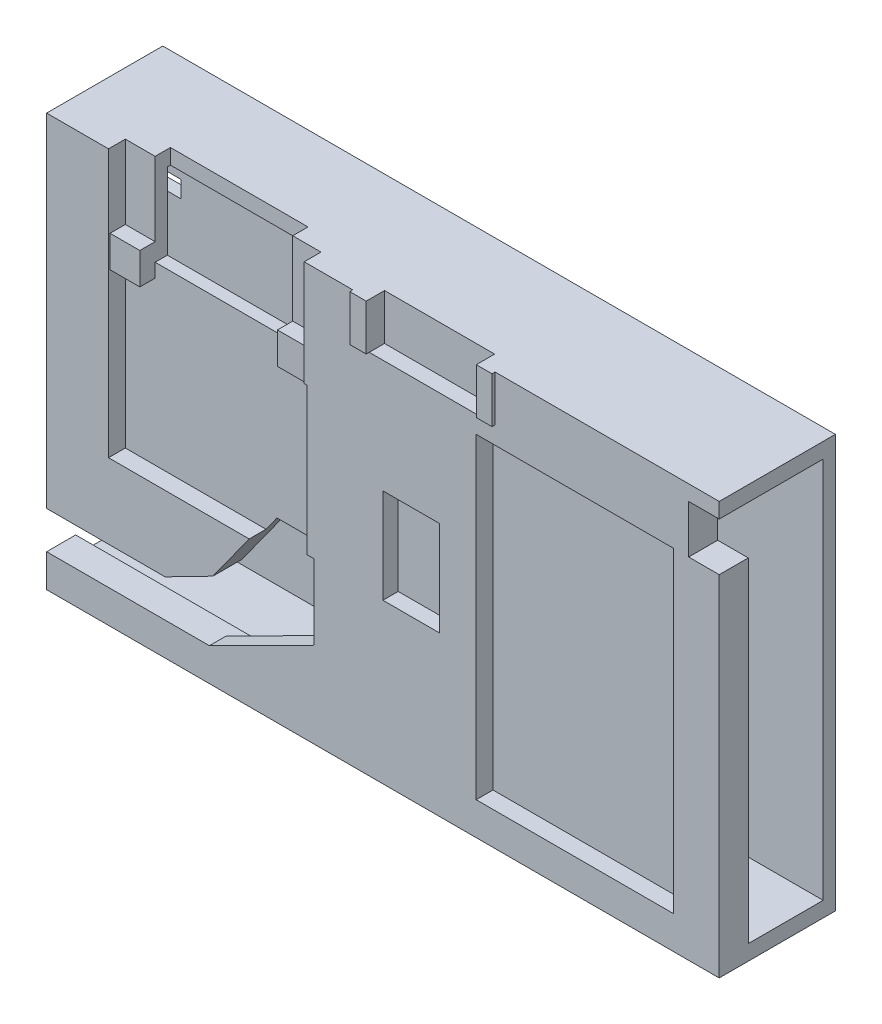
SolidWorks part; units mm, degrees
ref_plane "Plan de face" through (0, 0, 0) normal (0, 0, 1) x (1, 0, 0)
ref_plane "Plan de dessus" through (0, 0, 0) normal (0, 1, 0) x (1, 0, 0)
ref_plane "Plan de droite" through (0, 0, 0) normal (1, 0, 0) x (0, 0, -1)
sketch "Esquisse1" plane through (0, 0, 0) normal (0, 0, 1) x (1, 0, 0)
  line L1 (-22, -12.5) -> (22, -12.5)
  line L2 (-22, -12.5) -> (-22, 12.5)
  line L3 (-22, 12.5) -> (22, 12.5)
  line L4 (22, -12.5) -> (22, 12.5)
  line L5 (-22, -12.5) -> (22, 12.5) construction
  line L6 (-22, 12.5) -> (22, -12.5) construction
  point P0 (0, 0)
  dimension "D1" = 44
  dimension "D2" = 25
extrude "Boss.-Extru.1" add sketch "Esquisse1" along normal blind 1.9
sketch "Esquisse2" plane through (0, 0, 1.9) normal (0, 0, 1) x (1, 0, 0)
  line L0 (-22, 12.5) -> (-22, -12.5) construction
  line L1 (22, -12.5) -> (22, 12.5) construction
  line L3 (0.5, -12.5) -> (1.5, -12.5)
  line L11 (-2.5, 12.5014) -> (-20.5, 12.5014)
  line L12 (-2.5, 12.5014) -> (-2.5, -8.8986)
  line L13 (-2.5, -8.8986) -> (-20.5, -8.8986)
  line L14 (-20.5, 12.5014) -> (-20.5, -8.8986)
  line L16 (6.1, -11.3493) -> (19, -11.3493)
  line L17 (6.1, -11.3493) -> (6.1, 9.3507)
  line L18 (6.1, 9.3507) -> (19, 9.3507)
  line L19 (19, -11.3493) -> (19, 9.3507)
  line L20 (6.1, -11.3493) -> (19, 9.3507) construction
  line L21 (6.1, 9.3507) -> (19, -11.3493) construction
  point P5 (1, 0)
  point P19 (12.55, -0.9993)
  dimension "D1" = 18
  dimension "D2" = 1.5
  dimension "D3" = 3
  dimension "D4" = 12.9
  dimension "D5" = 20.7
extrude "Enlèv. mat.-Extru.1" cut sketch "Esquisse2" against normal blind 1.1 contours L12 L11 L14 L13 | L17 L16 L19 L18
sketch "Esquisse3" plane through (0, 0, 0.8) normal (0, 0, 1) x (1, 0, 0)
  line L0 (-20.5, 12.5) -> (-2.5, -8.8986)
  line L1 (-2.5, -8.8986) -> (-20.5, -8.8986)
  line L2 (-20.5, -8.8986) -> (-2.5, 12.5)
  line L3 (-2.5, 12.5) -> (-11.5, 1.8007)
  line L4 (-11.5, 1.8007) -> (-11.5, 14.3281)
  line L5 (-2.5, 12.5) -> (-20.5, 12.5) construction
  line L6 (-16, 18.5) -> (-7, 18.5)
  line L7 (-16, 18.5) -> (-16, 6.5)
  line L8 (-16, 6.5) -> (-7, 6.5)
  line L9 (-7, 18.5) -> (-7, 6.5)
  line L10 (-16, 18.5) -> (-7, 6.5) construction
  line L11 (-16, 6.5) -> (-7, 18.5) construction
  point P6 (-11.5, 12.5)
  dimension "D1" = 9
  dimension "D2" = 12
extrude "Enlèv. mat.-Extru.2" cut sketch "Esquisse3" against normal blind 10 contours L7 L6 L9 L8
sketch "Esquisse4" plane through (0, 0, 1.9) normal (0, 0, 1) x (1, 0, 0)
  line L0 (-2.5, -8.8986) -> (-2.5, -14.0676)
  line L1 (-4.5, -15.1841) -> (-4.5, -4.4659)
  line L2 (-8, -15.1841) -> (-8, -5.4707)
  line L3 (-19.2974, -5.6986) -> (1.333, -5.6986)
  line L4 (-2.5, -8.8986) -> (-20.5, -8.8986) construction
  line L5 (-22, -12.5) -> (22, -12.5) construction
  line L6 (-4.5, -5.6986) -> (-8, -5.6986)
  line L7 (-4.5, -5.6986) -> (-4.5, -12.5)
  line L8 (-4.5, -12.5) -> (-8, -12.5)
  line L9 (-8, -5.6986) -> (-8, -12.5)
  dimension "D1" = 2
  dimension "D2" = 3.5
  dimension "D3" = 3.2
extrude "Enlèv. mat.-Extru.3" cut sketch "Esquisse4" against normal blind 1.4 contours L7 L6 L9 L8
sketch "Esquisse5" plane through (0, 0, 1.9) normal (0, 0, 1) x (1, 0, 0)
  line L3 (-22, -12.5) -> (-8, -12.5) construction
  line L6 (-22, 12.5) -> (-22, -12.5) construction
  line L13 (-8, -5.6986) -> (-14.25, -8.8986)
  line L14 (-8, -8.8986) -> (-20.5, -8.8986) construction
  line L15 (-14.25, -8.8986) -> (-22, -8.8986)
  line L16 (-22, -8.8986) -> (-22, -12.5)
  line L17 (-4.5, -12.5) -> (-4.5, -5.6986)
  line L18 (-4.5, -5.6986) -> (-8, -5.6986)
  line L21 (-22, -12.5) -> (-4.5, -12.5)
extrude "Enlèv. mat.-Extru.4" cut sketch "Esquisse5" against normal blind 2.4
sketch "Esquisse6" plane through (0, 6.5, 0) normal (0, 1, 0) x (1, 0, 0)
  line L1 (-16, 0) -> (-7, 0)
  line L2 (-16, 0) -> (-16, -0.8)
  line L3 (-16, -0.8) -> (-7, -0.8)
  line L4 (-7, 0) -> (-7, -0.8)
extrude "Boss.-Extru.2" add sketch "Esquisse6" along normal blind 1
sketch "Esquisse7" plane through (0, -8.8986, 0) normal (0, 1, 0) x (1, 0, 0)
  line L0 (-2.5, -0.8) -> (-4.5, -0.8) construction
  line L1 (-2.5, -0.8) -> (-4.5, -0.8)
  line L2 (-2.5, -0.8) -> (-2.5, -1.9)
  line L3 (-2.5, -1.9) -> (-4.5, -1.9)
  line L4 (-4.5, -0.8) -> (-4.5, -1.9)
  line L5 (-2.5, -0.8) -> (-2.5, -1.9) construction
extrude "Boss.-Extru.3" add sketch "Esquisse7" along normal blind 1
sketch "Esquisse9" plane through (0, 12.5, 0) normal (0, 1, 0) x (1, 0, 0)
  line L1 (22, 0) -> (-2.5, 0)
  line L2 (22, 0) -> (22, -1.9)
  line L3 (22, -1.9) -> (-2.5, -1.9)
  line L4 (-2.5, -0.8) -> (-2.5, -1.9)
  line L5 (-7, 0) -> (-2.5, 0)
  line L6 (-7, 0) -> (-7, -0.8)
  line L7 (-7, -0.8) -> (-2.5, -0.8)
  line L9 (-22, 0) -> (-20.5, 0)
  line L10 (-22, 0) -> (-22, -1.9)
  line L11 (-22, -1.9) -> (-20.5, -1.9)
  line L12 (-20.5, -0.8) -> (-20.5, -1.9)
  line L13 (-16, -0.8) -> (-20.5, -0.8)
  line L14 (-16, -0.8) -> (-16, 0)
  line L15 (-16, 0) -> (-20.5, 0)
extrude "Boss.-Extru.4" add sketch "Esquisse9" along normal blind 1
sketch "Esquisse12" plane through (0, -12.5, 0) normal (0, -1, 0) x (1, 0, 0)
  line L1 (-4.5, 1.9) -> (22, 1.9)
  line L2 (-4.5, 1.9) -> (-4.5, 0)
  line L3 (-4.5, 0) -> (22, 0)
  line L4 (22, 1.9) -> (22, 0)
extrude "Boss.-Extru.6" add sketch "Esquisse12" along normal blind 1
sketch "Esquisse13" plane through (0, 0, 0) normal (0, 0, -1) x (-1, 0, 0)
  line L0 (22, 13.5) -> (22, -8.8986) construction
  line L1 (-22, 13.5) -> (22, 13.5)
  line L2 (-22, 13.5) -> (-22, 12.5)
  line L3 (-22, 12.5) -> (22, 12.5)
  line L4 (22, 13.5) -> (22, 12.5)
  line L6 (-22, -13.5) -> (22, -13.5)
  line L7 (-22, -13.5) -> (-22, -12.5)
  line L8 (-22, -12.5) -> (22, -12.5)
  line L9 (22, -13.5) -> (22, -12.5)
  dimension "D1" = 1
  dimension "D2" = 1
  dimension "D3" = 1
extrude "Boss.-Extru.7" add sketch "Esquisse13" along normal blind 4.9
sketch "Esquisse14" plane through (0, 0, -4.9) normal (0, 0, -1) x (-1, 0, 0)
  line L1 (-22, 13.5) -> (22, 13.5)
  line L2 (-22, 13.5) -> (-22, -13.5)
  line L3 (-22, -13.5) -> (22, -13.5)
  line L4 (22, 13.5) -> (22, -13.5)
extrude "Boss.-Extru.8" add sketch "Esquisse14" along normal blind 0.8
sketch "Esquisse15" plane through (0, 0, 0) normal (0, 0, 1) x (1, 0, 0)
  line L0 (-7, 13.5) -> (-7, 7.5) construction
  line L1 (-16, 13.5) -> (-7, 13.5)
  line L2 (-16, 13.5) -> (-16, 12.5)
  line L3 (-16, 12.5) -> (-7, 12.5)
  line L4 (-7, 13.5) -> (-7, 12.5)
  line L5 (22, 12.5) -> (-22, 12.5) construction
extrude "Enlèv. mat.-Extru.5" cut sketch "Esquisse15" against normal blind 0.2
sketch "Esquisse16" plane through (-22, 0, 0) normal (-1, 0, 0) x (0, 0, 1)
  line L0 (-5.7, -13.5) -> (-5.7, 13.5) construction
  line L1 (-4.9, 12.5) -> (-5.7, 12.5)
  line L2 (-4.9, 12.5) -> (-4.9, 11.4)
  line L3 (-4.9, 11.4) -> (-5.7, 11.4)
  line L4 (-5.7, 12.5) -> (-5.7, 11.4)
  dimension "D1" = 1.1
extrude "Enlèv. mat.-Extru.7" cut sketch "Esquisse16" against normal blind 2 contours L2 L1 L4 L3
sketch "Esquisse18" plane through (22, 0, 0) normal (1, 0, 0) x (0, 0, -1)
  line L0 (-1.9, -13.5) -> (-1.9, 13.5) construction
  line L1 (0, 12.5) -> (-1.9, 12.5)
  line L2 (0, 12.5) -> (0, 9.35)
  line L3 (0, 9.35) -> (-1.9, 9.35)
  line L4 (-1.9, 12.5) -> (-1.9, 9.35)
  dimension "D1" = 3.15
extrude "Enlèv. mat.-Extru.8" cut sketch "Esquisse18" against normal blind 2
sketch "Esquisse19" plane through (0, 0, -4.9) normal (0, 0, 1) x (1, 0, 0)
  line L0 (-22, -12.5) -> (22, -12.5) construction
  line L1 (-20, 12.5) -> (-19, 12.5)
  line L2 (-20, 12.5) -> (-20, -12.5)
  line L3 (-20, -12.5) -> (-19, -12.5)
  line L4 (-19, 12.5) -> (-19, -12.5)
  dimension "D1" = 1
extrude "Boss.-Extru.10" add sketch "Esquisse19" along normal blind 4.9
sketch "Esquisse20" plane through (0, 0, 0.8) normal (0, 0, 1) x (1, 0, 0)
  line L0 (-4.5, -5.6986) -> (-4.5, -7.8986) construction
  line L2 (-4.5, -5.7767) -> (-4.5, -3.0021)
  line L3 (-4.5, -3.0021) -> (-8.0283, -3.0021)
  line L5 (-8.0283, -3.0021) -> (-11.125, -7.2986)
  line L6 (-8, -5.6986) -> (-14.25, -8.8986) construction
  line L7 (-11.125, -7.2986) -> (-4.5, -5.7767)
extrude "Enlèv. mat.-Extru.9" cut sketch "Esquisse20" against normal blind 1
sketch "Esquisse21" plane through (-4.5, 0, 0) normal (-1, 0, 0) x (0, 0, 1)
  line L1 (0, -13.5) -> (1.9, -13.5)
  line L2 (0, -13.5) -> (0, -11.3493)
  line L3 (0, -11.3493) -> (1.9, -11.3493)
  line L4 (1.9, -13.5) -> (1.9, -11.3493)
extrude "Boss.-Extru.11" add sketch "Esquisse21" along normal blind 17.5 contours L2 L1 L4 L3
sketch "Esquisse23" plane through (0, 0, 0.8) normal (0, 0, 1) x (1, 0, 0)
  line L0 (-4.5, -7.8986) -> (-11.3488, -11.3493)
  line L1 (-22, -11.3493) -> (-4.5, -11.3493) construction
  line L2 (-11.3488, -11.3493) -> (-4.5, -11.3493)
  line L3 (-4.5, -11.3493) -> (-4.5, -7.8986)
extrude "Boss.-Extru.12" add sketch "Esquisse23" along normal blind 1.1
sketch "Esquisse25" plane through (0, 0, 0.8) normal (0, 0, 1) x (1, 0, 0)
  line L0 (-16, 13.5) -> (-20.5, 13.5)
  line L1 (-20.5, 13.5) -> (-20.5, -8.8986)
  line L2 (-20.5, -8.8986) -> (-14.25, -8.8986)
  line L3 (-14.25, -8.8986) -> (-11.125, -7.2986)
  line L4 (-11.125, -7.2986) -> (-8.0283, -3.0021)
  line L5 (-8.0283, -3.0021) -> (-4.5, -3.0021)
  line L6 (-4.5, -3.0021) -> (-4.5, -7.8986)
  line L7 (-4.5, -7.8986) -> (-2.5, -7.8986)
  line L8 (-2.5, -7.8986) -> (-2.5, 13.5)
  line L9 (-2.5, 13.5) -> (-7, 13.5)
  line L10 (-7, 13.5) -> (-7, 7.5)
  line L11 (-7, 7.5) -> (-16, 7.5)
  line L12 (-16, 7.5) -> (-16, 13.5)
extrude "Boss.-Extru.13" add sketch "Esquisse25" along normal blind 1.1
sketch "Esquisse26" plane through (0, 0, 1.9) normal (0, 0, 1) x (1, 0, 0)
  line L0 (-11.5, 7.5) -> (-11.5, -5.1399)
  line L1 (-7, 7.5) -> (-16, 7.5) construction
  line L3 (-17.95, -4) -> (-5.05, -4)
  line L4 (-17.95, -4) -> (-17.95, 13.5)
  line L5 (-17.95, 13.5) -> (-5.05, 13.5)
  line L6 (-5.05, -4) -> (-5.05, 13.5)
  line L7 (-17.95, -4) -> (-5.05, 13.5) construction
  line L8 (-17.95, 13.5) -> (-5.05, -4) construction
  line L9 (-22, 13.5) -> (-16, 13.5) construction
  point P4 (-11.5, 4.75)
  dimension "D1" = 12.9
  dimension "D2" = 17.5
  dimension "D3" = 0
extrude "Enlèv. mat.-Extru.10" cut sketch "Esquisse26" against normal blind 1.1 contours L4 L3 L6 L5
sketch "Esquisse28" plane through (-20, 0, 0) normal (-1, 0, 0) x (0, 0, 1)
  line L1 (0, 12.5) -> (-4.9, 12.5)
  line L2 (0, 12.5) -> (0, -12.5)
  line L3 (0, -12.5) -> (-4.9, -12.5)
  line L4 (-4.9, 12.5) -> (-4.9, -12.5)
extrude "Enlèv. mat.-Extru.12" cut sketch "Esquisse28" against normal blind 10
sketch "Esquisse30" plane through (-22, 0, 0) normal (-1, 0, 0) x (0, 0, 1)
  line L1 (0, 12.5) -> (-4.9, 12.5)
  line L2 (0, 12.5) -> (0, -12.5)
  line L3 (0, -12.5) -> (-4.9, -12.5)
  line L4 (-4.9, 12.5) -> (-4.9, -12.5)
extrude "Boss.-Extru.14" add sketch "Esquisse30" against normal blind 1
sketch "Esquisse31" plane through (-21, 0, 0) normal (1, 0, 0) x (0, 0, -1)
  line L0 (4.9, 11.4) -> (4.9, -12.5) construction
  line L1 (0, 12.5) -> (4.9, 12.5)
  line L2 (0, 12.5) -> (0, 7.722)
  line L3 (0, 7.722) -> (4.9, 7.722)
  line L4 (4.9, 12.5) -> (4.9, 7.722)
  line L6 (0, -12.5) -> (4.9, -12.5)
  line L7 (0, -12.5) -> (0, -7.7224)
  line L8 (0, -7.7224) -> (4.9, -7.7224)
  line L9 (4.9, -12.5) -> (4.9, -7.7224)
extrude "Enlèv. mat.-Extru.13" cut sketch "Esquisse31" against normal blind 11
sketch "Esquisse32" plane through (0, 0, -5.7) normal (0, 0, -1) x (-1, 0, 0)
  line L0 (22, -13.5) -> (22, 11.4) construction
  line L1 (22, 10.0654) -> (20, 10.0654)
  line L2 (22, 10.0654) -> (22, 8.9654)
  line L3 (22, 8.9654) -> (20, 8.9654)
  line L4 (20, 10.0654) -> (20, 8.9654)
  line L6 (22, 7.3356) -> (20, 7.3356)
  line L7 (22, 7.3356) -> (22, 6.2356)
  line L8 (22, 6.2356) -> (20, 6.2356)
  line L9 (20, 7.3356) -> (20, 6.2356)
  dimension "D1" = 1.1
  dimension "D2" = 1.1
  dimension "D3" = 2
  dimension "D4" = 2
extrude "Enlèv. mat.-Extru.14" cut sketch "Esquisse32" against normal blind 5
sketch "Esquisse33" plane through (-22, 0, 0) normal (-1, 0, 0) x (0, 0, 1)
  line L1 (0, 12.5) -> (-4.88, 12.5)
  line L2 (0, 12.5) -> (0, 2.8897)
  line L3 (0, 2.8897) -> (-4.88, 2.8897)
  line L4 (-4.88, 12.5) -> (-4.88, 2.8897)
extrude "Enlèv. mat.-Extru.15" cut sketch "Esquisse33" against normal blind 5
sketch "Esquisse34" plane through (-22, 0, 0) normal (-1, 0, 0) x (0, 0, 1)
  line L0 (-4.9, -7.7224) -> (0, -7.7224) construction
  line L1 (-3.1462, -7.7224) -> (-2.0462, -7.7224)
  line L2 (-3.1462, -7.7224) -> (-3.1462, 2.8897)
  line L3 (-3.1462, 2.8897) -> (-2.0462, 2.8897)
  line L4 (-2.0462, -7.7224) -> (-2.0462, 2.8897)
  line L5 (-4.88, 2.8897) -> (0, 2.8897) construction
  dimension "D1" = 1.1
extrude "Enlèv. mat.-Extru.16" cut sketch "Esquisse34" against normal blind 5
sketch "Esquisse35" plane through (-5.05, 0, 0) normal (-1, 0, 0) x (0, 0, 1)
  line L1 (0.8, 13.5) -> (1.9, 13.5)
  line L2 (0.8, 13.5) -> (0.8, -3.0021)
  line L3 (0.8, -3.0021) -> (1.9, -3.0021)
  line L4 (1.9, 13.5) -> (1.9, -3.0021)
extrude "Boss.-Extru.15" add sketch "Esquisse35" along normal blind 0.1
sketch "Esquisse36" plane through (0, 0, 0.8) normal (0, 0, 1) x (1, 0, 0)
  line L4 (-17.95, -4) -> (-17.95, 13.5) construction
  line L5 (-16, 6.6) -> (-17.95, 6.6)
  line L6 (-16, 6.6) -> (-16, 8.6651)
  line L7 (-16, 8.6651) -> (-17.95, 8.6651)
  line L8 (-17.95, 6.6) -> (-17.95, 8.6651)
  line L9 (-7, 7.5) -> (-7, 13.5) construction
  line L10 (-7, 8.6651) -> (-5.1566, 8.6651)
  line L11 (-7, 8.6651) -> (-7, 6.6)
  line L12 (-7, 6.6) -> (-5.1566, 6.6)
  line L13 (-5.1566, 8.6651) -> (-5.1566, 6.6)
extrude "Boss.-Extru.16" add sketch "Esquisse36" along normal blind 1
sketch "Esquisse37" plane through (20, 0, 0) normal (1, 0, 0) x (0, 0, -1)
  line L1 (0, 12.5) -> (-1.9, 12.5)
  line L2 (0, 12.5) -> (0, 9.35)
  line L3 (0, 9.35) -> (-1.9, 9.35)
  line L4 (-1.9, 12.5) -> (-1.9, 9.35)
sketch "Esquisse38" plane through (22, 0, 0) normal (1, 0, 0) x (0, 0, -1)
  line L1 (5.7, 13.5) -> (-1.9, 13.5)
  line L2 (5.7, 13.5) -> (5.7, -13.5)
  line L3 (5.7, -13.5) -> (-1.9, -13.5)
  line L4 (-1.9, 13.5) -> (-1.9, -13.5)
sketch "Esquisse39" plane through (0, 0, 1.9) normal (0, 0, 1) x (1, 0, 0)
  line L0 (-3.2523, 12.125) -> (10.5301, 12.125)
  line L1 (1.1, 7.5962) -> (1.1, 12.1448)
  line L2 (4.1, 8.0056) -> (4.1, 12.1448)
  line L3 (-5.15, 13.5) -> (22, 13.5) construction
  line L4 (6.1, -11.3493) -> (6.1, 9.3507) construction
  line L6 (-0.894, 13.5) -> (6.306, 13.5)
  line L7 (-0.894, 13.5) -> (-0.894, 10.5)
  line L8 (-0.894, 10.5) -> (6.306, 10.5)
  line L9 (6.306, 13.5) -> (6.306, 10.5)
  circle A0 centre (1.1, 12.1448) radius 0.5
  circle A1 centre (4.1, 12.1448) radius 0.5
  dimension "D3" = 1
  dimension "D4" = 1
  dimension "D1" = 3
  dimension "D2" = 1.375
  dimension "D5" = 2
  dimension "D6" = 7.2
  dimension "D7" = 3
sketch "Esquisse40" plane through (0, 0, 1.9) normal (0, 0, 1) x (1, 0, 0)
  line L1 (3.7, -3.1) -> (0, -3.1)
  line L2 (3.7, -3.1) -> (3.7, 3.1)
  line L3 (3.7, 3.1) -> (0, 3.1)
  line L4 (0, -3.1) -> (0, 3.1)
  line L5 (3.7, -3.1) -> (0, 3.1) construction
  line L6 (3.7, 3.1) -> (0, -3.1) construction
  point P0 (1.85, 0)
  dimension "D1" = 3.7
  dimension "D2" = 6.2
  dimension "D3" = 0
  dimension "D4" = 3.1
extrude "Enlèv. mat.-Extru.18" cut sketch "Esquisse40" against normal blind 1
extrude "Enlèv. mat.-Extru.20" cut sketch "Esquisse39" against normal blind 1 contours L7 L6 L9 L8
sketch "Esquisse41" plane through (0, 0, 1.9) normal (0, 0, 1) x (1, 0, 0)
  line L1 (-0.894, 13.5) -> (-1.9661, 13.5)
  line L2 (-0.894, 13.5) -> (-0.894, 10.5022)
  line L3 (-0.894, 10.5022) -> (-1.9661, 10.5022)
  line L4 (-1.9661, 13.5) -> (-1.9661, 10.5022)
  line L5 (6.306, 13.5) -> (7.3395, 13.5)
  line L6 (6.306, 13.5) -> (6.306, 10.5022)
  line L7 (6.306, 10.5022) -> (7.3395, 10.5022)
  line L8 (7.3395, 13.5) -> (7.3395, 10.5022)
extrude "Boss.-Extru.17" add sketch "Esquisse41" along normal blind 0.2
sketch "Esquisse42" plane through (-5.15, 0, 0) normal (-1, 0, 0) x (0, 0, 1)
  line L0 (0.8, 13.5) -> (0.8, -3.0021) construction
  line L1 (1.9, -3.0021) -> (0.8, -3.0021)
  line L2 (1.9, -3.0021) -> (1.9, 6.6004)
  line L3 (1.9, 6.6004) -> (0.8, 6.6004)
  line L4 (0.8, -3.0021) -> (0.8, 6.6004)
extrude "Enlèv. mat.-Extru.21" cut sketch "Esquisse42" against normal blind 0.2
sketch "Esquisse43" plane through (0, 0, 1.9) normal (0, 0, 1) x (1, 0, 0)
  line L2 (-22, 13.5) -> (-22, -13.5)
